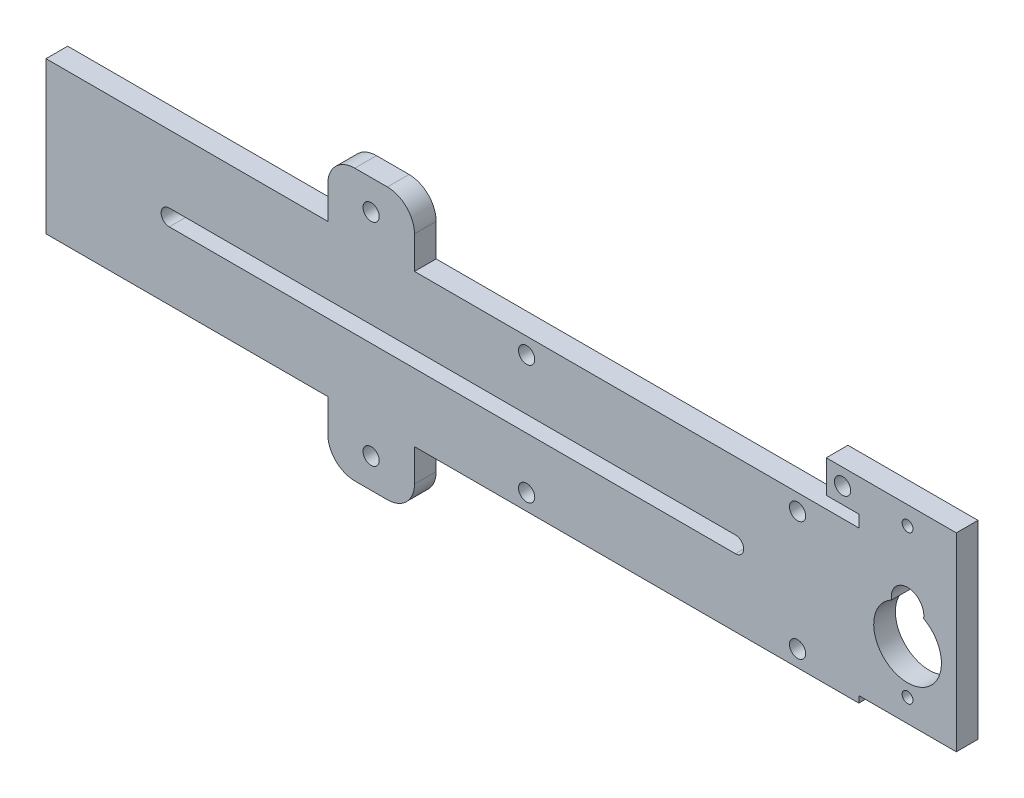
SolidWorks part; units mm, degrees
ref_plane "Спереди" through (0, 0, 0) normal (0, 0, 1) x (1, 0, 0)
ref_plane "Сверху" through (0, 0, 0) normal (0, 1, 0) x (1, 0, 0)
ref_plane "Справа" through (0, 0, 0) normal (1, 0, 0) x (0, 0, -1)
sketch "Эскиз1" plane through (0, 0, 0) normal (0, 0, 1) x (1, 0, 0)
  line L1 (-75, 14) -> (75, 14)
  line L2 (-75, 14) -> (-75, -14)
  line L3 (-75, -14) -> (75, -14)
  line L4 (75, 14) -> (75, -14)
  line L5 (-75, 14) -> (75, -14) construction
  line L6 (-75, -14) -> (75, 14) construction
  point P0 (0, 0)
  dimension "D1" = 28
  dimension "D2" = 150
extrude "Бобышка-Вытянуть1" add sketch "Эскиз1" along normal blind 4 contours L1 L4 L3 L2
sketch "Эскиз2" plane through (0, 0, 4) normal (0, 0, 1) x (1, 0, 0)
  line L0 (-52.2515, 0) -> (52.2515, 0) construction
  line L1 (-52.2515, 1.5) -> (52.2515, 1.5)
  line L2 (-52.2515, -1.5) -> (52.2515, -1.5)
  arc A0 (-52.2515, 1.5) -> (-52.2515, -1.5) centre (-52.2515, 0) ccw
  arc A1 (52.2515, -1.5) -> (52.2515, 1.5) centre (52.2515, 0) ccw
  point P2 (0, 0)
  dimension "D1" = 1.5
extrude "Вырез-Вытянуть1" cut sketch "Эскиз2" against normal through all contours L2 A1 L1 A0
sketch "Эскиз4" plane through (0, 0, 4) normal (0, 0, 1) x (1, 0, 0)
  line L0 (13.6122, -9.0038) -> (71.6122, -9.0038) construction
  line L1 (13.6122, -9.0038) -> (71.6122, -9.0038) construction
  line L2 (0, 0) -> (87.9644, 0) construction
  circle A0 centre (13.6991, -11.0038) radius 1.5 construction
  circle A1 centre (13.6991, -11.0038) radius 1.5
  circle A2 centre (63.6991, -11.0038) radius 1.5 construction
  circle A3 centre (63.6991, -11.0038) radius 1.5
  circle A4 centre (63.6991, 11.0038) radius 1.5
  circle A5 centre (13.6991, 11.0038) radius 1.5
extrude "Вырез-Вытянуть2" cut sketch "Эскиз4" against normal through all
sketch "Эскиз5" plane through (0, 0, 0) normal (0, 0, -1) x (-1, 0, 0)
  line L0 (-84, 0) -> (-84, 6) construction
  line L2 (-75, -12.7853) -> (-93, -12.7853)
  line L3 (-75, -12.7853) -> (-75, 22.2147)
  line L4 (-75, 22.2147) -> (-93, 22.2147)
  line L5 (-93, -12.7853) -> (-93, 22.2147)
  line L6 (0, 0) -> (-116.4397, 0) construction
  line L7 (-75, 14) -> (-75, -14) construction
  circle A0 centre (-84, 0) radius 6.25
  circle A1 centre (-84, 6) radius 3
  circle A3 centre (-84, -8.575) radius 1 construction
  circle A4 centre (-84, 18.825) radius 1 construction
  circle A5 centre (-84, -8.575) radius 1
  circle A6 centre (-84, 18.825) radius 1
  point P8 (-84, -12.7853)
  line M16 (-75, 14) -> (-75, -14)
  dimension "D1" = 6
  dimension "D2" = 6
  dimension "D3" = 12.5
  dimension "D4" = 35
  dimension "D5" = 18
extrude "Бобышка-Вытянуть3" add sketch "Эскиз5" against normal up to surface (4 mm away) contours L5 L2 L3 L4 A1 A0 M16
sketch "Эскиз7" plane through (0, 0, 4) normal (0, 0, 1) x (1, 0, 0)
  line L0 (75, 22.2147) -> (75, 14) construction
  line L1 (75, 22.2147) -> (69, 22.2147)
  line L2 (75, 22.2147) -> (75, 16.2147)
  line L3 (75, 16.2147) -> (69, 16.2147)
  line L4 (69, 22.2147) -> (69, 16.2147)
  line L5 (75, 22.2147) -> (69, 16.2147) construction
  line L6 (75, 16.2147) -> (69, 22.2147) construction
  line L7 (75, 22.2147) -> (93, 22.2147) construction
  circle A0 centre (72, 19.2147) radius 1.5
  point P0 (72, 19.2147)
  dimension "D3" = 3
  dimension "D1" = 6
  dimension "D2" = 6
extrude "Бобышка-Вытянуть4" add sketch "Эскиз7" against normal up to surface (4 mm away) contours A0
sketch "Эскиз3" plane through (0, 0, 4) normal (0, 0, 1) x (1, 0, 0)
  line L1 (-7, 25) -> (-23, 25)
  line L2 (-7, 25) -> (-7, -25)
  line L3 (-7, -25) -> (-23, -25)
  line L4 (-23, 25) -> (-23, -25)
  line L5 (-7, 25) -> (-23, -25) construction
  line L6 (-7, -25) -> (-23, 25) construction
  line L7 (0, 0) -> (-133.9775, 0) construction
  line L8 (-23, -14) -> (-7, -25) construction
  line L9 (-75, -14) -> (75, -14) construction
  line L10 (-7, -4) -> (-23, -4)
  line L11 (-7, -4) -> (-7, 4)
  line L12 (-7, 4) -> (-23, 4)
  line L13 (-23, -4) -> (-23, 4)
  line L14 (-7, -4) -> (-23, 4) construction
  line L15 (-7, 4) -> (-23, -4) construction
  line L16 (-75, 14) -> (-75, -14) construction
  circle A0 centre (-15, 19.5) radius 1.5
  circle A1 centre (-15, -19.5) radius 1.5
  point P0 (-15, 0)
  point P15 (-15, 0)
  line M13 (-75, -14) -> (75, -14)
  line M15 (75, 14) -> (-75, 14)
  dimension "D2" = 3
  dimension "D1" = 50
  dimension "D3" = 8
  dimension "D4" = 60
  dimension "D5" = 16
extrude "Бобышка-Вытянуть2" add sketch "Эскиз3" against normal up to surface (4 mm away) contours L12 L2 L4 M15 | L1 L4 L2 A0 M15 | L2 L10 L4 M13 | L4 L3 L2 A1 M13 up to face at (12.1991, 11.0038, 0)
fillet "Скругление1" radius 5 4 edges at (-23, 25, 2) (-7, 25, 2) (-7, -25, 2) (-23, -25, 2)
